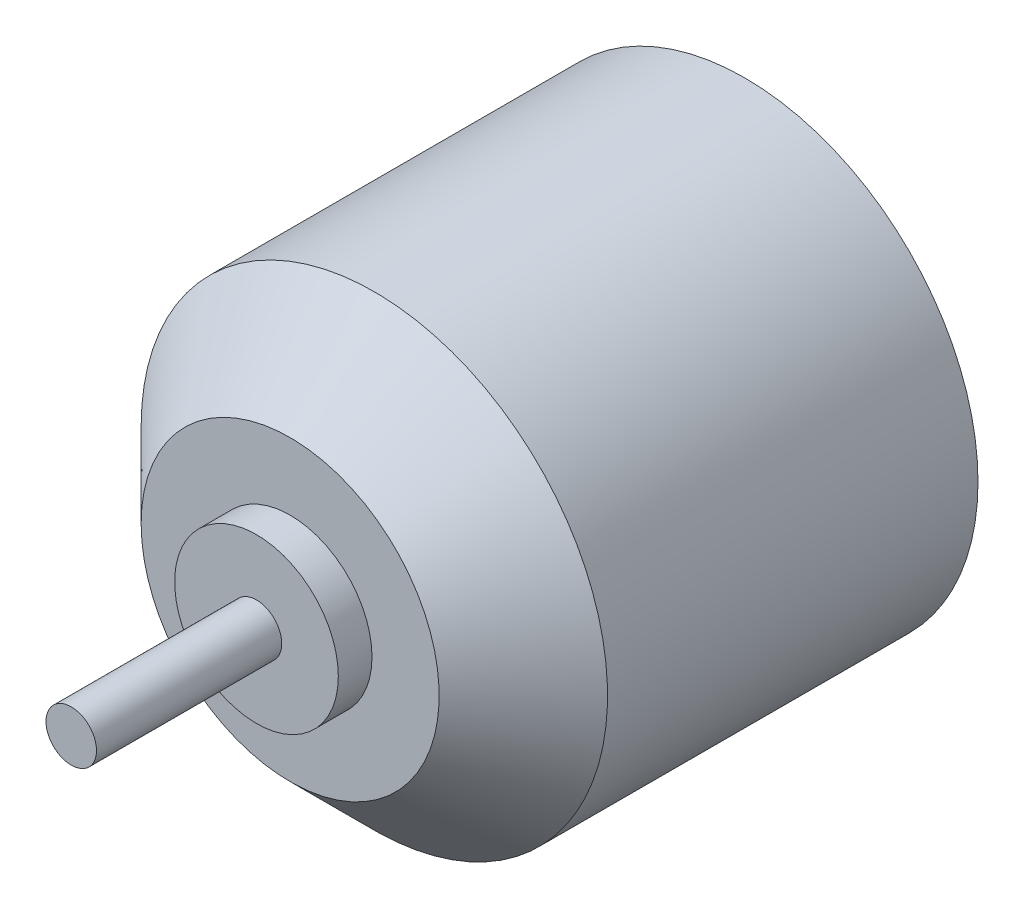
SolidWorks part; units mm, degrees
ref_plane "Plan de face" through (0, 0, 0) normal (0, 0, 1) x (1, 0, 0)
ref_plane "Plan de dessus" through (0, 0, 0) normal (0, 1, 0) x (1, 0, 0)
ref_plane "Plan de droite" through (0, 0, 0) normal (1, 0, 0) x (0, 0, -1)
sketch "Esquisse1" plane through (0, 0, 0) normal (0, 0, 1) x (1, 0, 0)
  circle A0 centre (0, 0) radius 13.85
  dimension "D1" = 27.7
extrude "Boss.-Extru.1" add sketch "Esquisse1" along normal blind 27
chamfer "Chanfrein1" distance 5 angle 45 1 edges at (13.85, 0, 27)
sketch "Esquisse2" plane through (0, 0, 27) normal (0, 0, 1) x (1, 0, 0)
  circle A0 centre (0, 0) radius 1.5
  dimension "D1" = 3
extrude "Boss.-Extru.2" add sketch "Esquisse2" along normal blind 13
sketch "Esquisse3" plane through (0, 0, 27) normal (0, 0, 1) x (1, 0, 0)
  circle A0 centre (0, 0) radius 4.8602
extrude "Boss.-Extru.3" add sketch "Esquisse3" along normal blind 2
